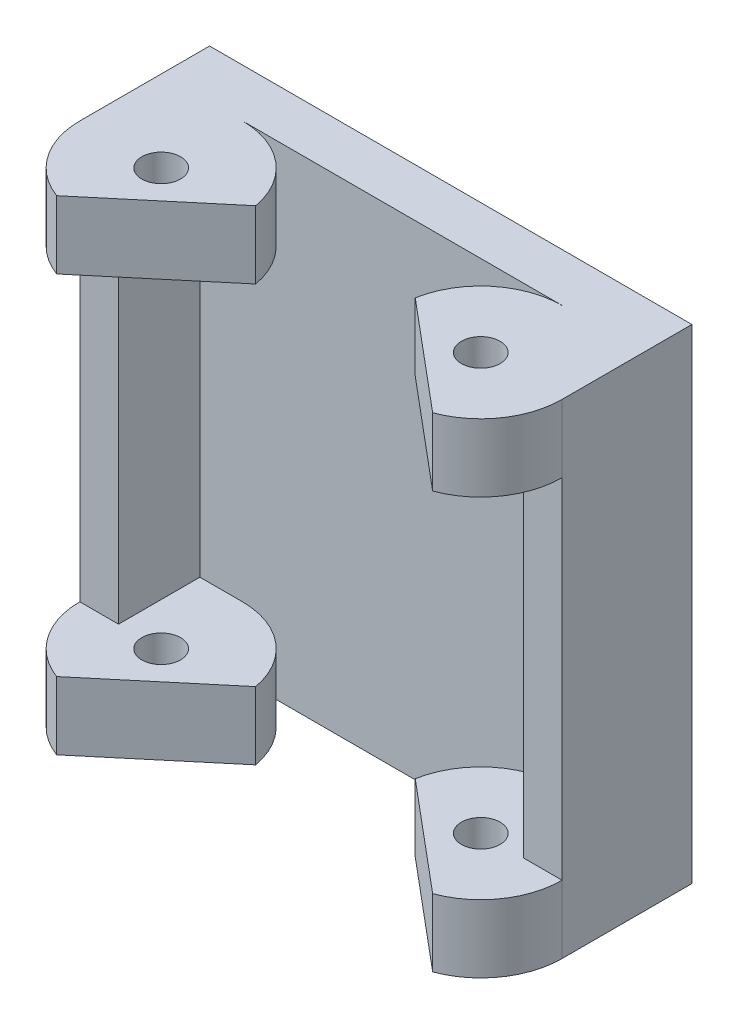
SolidWorks part; units mm, degrees
ref_plane "Front Plane" through (0, 0, 0) normal (0, 0, 1) x (1, 0, 0)
ref_plane "Top Plane" through (0, 0, 0) normal (0, 1, 0) x (1, 0, 0)
ref_plane "Right Plane" through (0, 0, 0) normal (1, 0, 0) x (0, 0, -1)
sketch "Sketch1" plane through (0, 0, 0) normal (0, 1, 0) x (1, 0, 0)
  line L0 (0, 22.8391) -> (0, -19.8342) construction
  line L1 (-35.1495, 0) -> (37.3645, 0) construction
  line L2 (-24.9, 0) -> (-24.9, 13.4)
  line L3 (-24.9, 13.4) -> (24.9, 13.4)
  line L4 (24.9, 0) -> (24.9, 13.4)
  line L5 (-19.4124, -7.879) -> (-8.235, 1.5)
  line L6 (19.4124, -7.879) -> (8.235, 1.5)
  line L7 (16.5, 8.4) -> (-16.5, 8.4)
  arc A0 (19.4124, -7.879) -> (24.9, 0) centre (16.5, 0) ccw
  arc A1 (-19.4124, -7.879) -> (-24.9, 0) centre (-16.5, 0) cw
  arc A2 (-16.5, 8.4) -> (-8.235, 1.5) centre (-16.5, 0) cw
  arc A3 (16.5, 8.4) -> (8.235, 1.5) centre (16.5, 0) ccw
  circle A4 centre (-16.5, 0) radius 8.4 construction
  circle A5 centre (16.5, 0) radius 8.4 construction
  point P14 (0, 13.4)
  point P16 (-20.4749, 7.4)
  dimension "D1" = 16.8
  dimension "D2" = 33
  dimension "D3" = 5
  dimension "D4" = 130
  dimension "D5" = 1.5
  dimension "D6" = 13.4
extrude "Boss-Extrude2" add sketch "Sketch1" along normal blind 7
sketch "Sketch3" plane through (0, 7, 0) normal (0, 1, 0) x (1, 0, 0)
  circle A0 centre (-16.5, 0) radius 2
  circle A1 centre (16.5, 0) radius 2
  dimension "D1" = 4
extrude "Cut-Extrude2" cut sketch "Sketch3" against normal through all both and the other way through all
sketch "Sketch4" plane through (0, 7, 0) normal (0, 1, 0) x (1, 0, 0)
  line L0 (-24.9, 13.4) -> (-24.9, 0)
  line L1 (-24.9, 13.4) -> (24.9, 13.4)
  line L2 (24.9, 13.4) -> (24.9, 0)
  line L3 (0, 13.4) -> (0, 0) construction
  line L4 (-16.5, 8.4) -> (16.5, 8.4)
  line L5 (-16.5, 8.4) -> (16.5, 8.4) construction
  line L6 (16.5, 8.4) -> (20.9, 8.4)
  line L7 (20.9, 8.4) -> (20.9, 0)
  line L8 (20.9, 0) -> (24.9, 0)
  line L9 (-20.9, 0) -> (-24.9, 0)
  line L10 (-20.9, 8.4) -> (-20.9, 0)
  line L11 (-16.5, 8.4) -> (-20.9, 8.4)
  circle A0 centre (-16.5, 0) radius 3.7 construction
  point P21 (0, 8.4)
  dimension "D2" = 7.4
  dimension "D1" = 4
extrude "Boss-Extrude3" add sketch "Sketch4" along normal blind 36
sketch "Sketch5" plane through (0, 43, 0) normal (0, 1, 0) x (1, 0, 0)
  line L12 (-24.9, 13.4) -> (-24.9, 0)
  line L13 (24.9, 13.4) -> (-24.9, 13.4)
  line L14 (24.9, 0) -> (24.9, 13.4)
  line L15 (8.235, 1.5) -> (19.4124, -7.879)
  line L16 (-16.5, 8.4) -> (16.5, 8.4)
  line L17 (-19.4124, -7.879) -> (-8.235, 1.5)
  line L18 (-24.9, 13.4) -> (-24.9, 0)
  line L19 (24.9, 13.4) -> (-24.9, 13.4)
  line L20 (24.9, 0) -> (24.9, 13.4)
  line L21 (8.235, 1.5) -> (19.4124, -7.879)
  line L22 (-16.5, 8.4) -> (16.5, 8.4)
  line L23 (-19.4124, -7.879) -> (-8.235, 1.5)
  circle A0 centre (-16.5, 0) radius 2 construction
  circle A1 centre (16.5, 0) radius 2
  circle A2 centre (16.5, 0) radius 2 construction
  circle A4 centre (-16.5, 0) radius 2
  arc A8 (-24.9, 0) -> (-19.4124, -7.879) centre (-16.5, 0) ccw
  arc A9 (19.4124, -7.879) -> (24.9, 0) centre (16.5, 0) ccw
  arc A10 (16.5, 8.4) -> (8.235, 1.5) centre (16.5, 0) ccw
  arc A11 (-8.235, 1.5) -> (-16.5, 8.4) centre (-16.5, 0) ccw
  arc A12 (-24.9, 0) -> (-19.4124, -7.879) centre (-16.5, 0) ccw
  arc A13 (19.4124, -7.879) -> (24.9, 0) centre (16.5, 0) ccw
  arc A14 (16.5, 8.4) -> (8.235, 1.5) centre (16.5, 0) ccw
  arc A15 (-8.235, 1.5) -> (-16.5, 8.4) centre (-16.5, 0) ccw
  dimension "D1" = 0
extrude "Boss-Extrude4" add sketch "Sketch5" along normal blind 7
sketch "Sketch13" plane through (0, 50, 0) normal (0, 1, 0) x (1, 0, 0)
  line L0 (24.9, 0) -> (24.9, 13.4) construction
  line L5 (-24.9, 13.4) -> (24.9, 13.4)
  line L6 (-24.9, 13.4) -> (-24.9, 8.4)
  line L7 (-24.9, 8.4) -> (24.9, 8.4)
  line L8 (24.9, 13.4) -> (24.9, 8.4)
  line L9 (-16.5, 8.4) -> (16.5, 8.4) construction
extrude "Boss-Extrude6" [suppressed] add sketch "Sketch13" along normal blind 12.8
sketch "Sketch12" plane through (0, 0, -13.4) normal (0, 0, -1) x (-1, 0, 0)
  line L0 (-24.9, 0) -> (24.9, 0)
  line L1 (24.9, 0) -> (24.9, -11.4972)
  line L3 (-24.9, 0) -> (-73.6185, 11.2476)
  line L4 (-73.6185, 11.2476) -> (-84.8661, -37.471)
  line L5 (-84.8661, -37.471) -> (62.371, -71.4633)
  line L6 (62.371, -71.4633) -> (73.6185, -22.7448)
  line L7 (73.6185, -22.7448) -> (24.9, -11.4972)
  line L8 (-24.9, 7) -> (-24.9, 0) construction
  point P4 (0, 0)
  point P10 (0, 0)
  point P11 (0, 0)
  point P12 (0, 0)
  dimension "D1" = 50
  dimension "D2" = 50
  dimension "D3" = 50
  dimension "D4" = 77
extrude "Boss-Extrude5" [suppressed] add sketch "Sketch12" against normal blind 5 separate body
combine bodies "Combine2" [suppressed] operation type add bodies to combine 111 110
